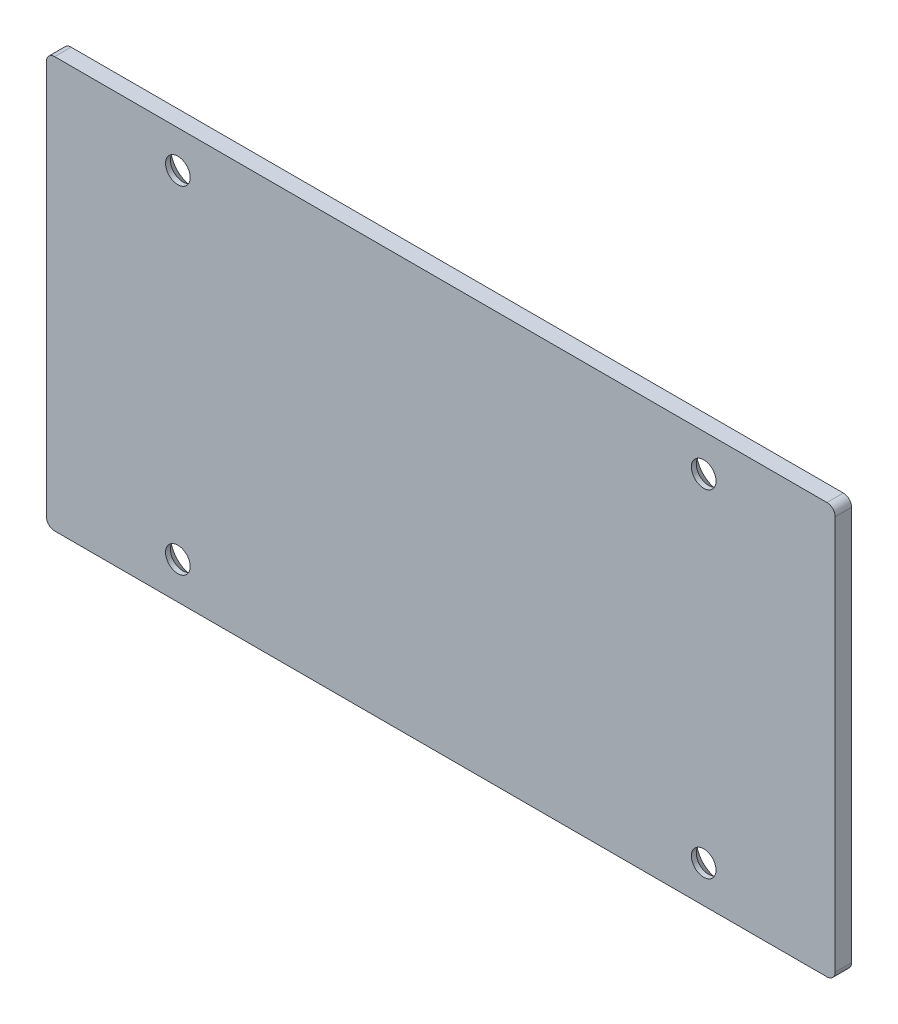
SolidWorks part; units mm, degrees
ref_plane "Спереди" through (0, 0, 0) normal (0, 0, 1) x (1, 0, 0)
ref_plane "Сверху" through (0, 0, 0) normal (0, 1, 0) x (1, 0, 0)
ref_plane "Справа" through (0, 0, 0) normal (1, 0, 0) x (0, 0, -1)
sketch "Эскиз1" plane through (0, 0, 60.7538) normal (0, 0, -1) x (-1, 0, 0)
  line L0 (-84.5501, 64.5438) -> (-84.5501, 29.5438)
  line L17 (-1.5112, 29.1447) -> (-7.5891, 29.1447)
  line L18 (-9.3198, 24.0438) -> (-63.7804, 24.0438)
  line L19 (-73.3198, 24.0438) -> (-82.5501, 24.0438)
  line L20 (-82.5501, 24.0438) -> (-82.5501, 29.5438)
  line L21 (-82.5501, 29.5438) -> (-84.5501, 29.5438)
  line L22 (-84.5501, 29.5438) -> (-84.5501, 23.0438)
  line L23 (-83.5501, 22.0438) -> (10.4499, 22.0438)
  line L24 (11.4499, 23.0438) -> (11.4499, 71.0438)
  line L25 (10.4499, 72.0438) -> (-83.5501, 72.0438)
  line L26 (-84.5501, 71.0438) -> (-84.5501, 64.5438)
  line L27 (-84.5501, 64.5438) -> (-82.5501, 64.5438)
  line L28 (-82.5501, 64.5438) -> (-82.5501, 70.0438)
  line L29 (-82.5501, 70.0438) -> (-73.3198, 70.0438)
  line L31 (0.2196, 70.0438) -> (9.4499, 70.0438)
  line L32 (9.4499, 70.0438) -> (9.4499, 24.0438)
  line L33 (9.4499, 24.0438) -> (0.2196, 24.0438)
  line L35 (-63.7804, 70.0438) -> (-9.3198, 70.0438)
  line L39 (-84.5501, 29.5438) -> (-84.5501, 23.0438)
  line L40 (-83.5501, 22.0438) -> (10.4499, 22.0438)
  line L41 (11.4499, 23.0438) -> (11.4499, 71.0438)
  line L42 (10.4499, 72.0438) -> (-83.5501, 72.0438)
  line L43 (-84.5501, 71.0438) -> (-84.5501, 64.5438)
  circle A0 centre (-4.5501, 67.5438) radius 1.5
  circle A1 centre (-68.5501, 67.5438) radius 1.5
  circle A2 centre (-68.5501, 26.5438) radius 1.5
  circle A3 centre (-4.5501, 26.5438) radius 1.5
  arc A9 (-0.7344, 25.3438) -> (-1.5112, 29.1447) centre (-4.5501, 26.5438) ccw
  arc A10 (-7.5891, 29.1447) -> (-8.3659, 25.3438) centre (-4.5501, 26.5438) ccw
  arc A11 (-64.7344, 25.3438) -> (-72.3659, 25.3438) centre (-68.5501, 26.5438) ccw
  arc A12 (-84.5501, 23.0438) -> (-83.5501, 22.0438) centre (-83.5501, 23.0438) ccw
  arc A13 (10.4499, 22.0438) -> (11.4499, 23.0438) centre (10.4499, 23.0438) ccw
  arc A14 (11.4499, 71.0438) -> (10.4499, 72.0438) centre (10.4499, 71.0438) ccw
  arc A15 (-83.5501, 72.0438) -> (-84.5501, 71.0438) centre (-83.5501, 71.0438) ccw
  arc A16 (-72.3659, 68.7438) -> (-64.7344, 68.7438) centre (-68.5501, 67.5438) ccw
  arc A17 (-8.3659, 68.7438) -> (-0.7344, 68.7438) centre (-4.5501, 67.5438) ccw
  arc A21 (-84.5501, 23.0438) -> (-83.5501, 22.0438) centre (-83.5501, 23.0438) ccw
  arc A22 (10.4499, 22.0438) -> (11.4499, 23.0438) centre (10.4499, 23.0438) ccw
  arc A23 (11.4499, 71.0438) -> (10.4499, 72.0438) centre (10.4499, 71.0438) ccw
  arc A24 (-83.5501, 72.0438) -> (-84.5501, 71.0438) centre (-83.5501, 71.0438) ccw
  arc A34 (-9.3198, 24.0438) -> (-8.3659, 25.3438) centre (-9.3198, 25.0438) ccw
  arc A36 (-64.7344, 25.3438) -> (-63.7804, 24.0438) centre (-63.7804, 25.0438) ccw
  arc A38 (-73.3198, 24.0438) -> (-72.3659, 25.3438) centre (-73.3198, 25.0438) ccw
  arc A40 (-72.3659, 68.7438) -> (-73.3198, 70.0438) centre (-73.3198, 69.0438) ccw
  arc A42 (-63.7804, 70.0438) -> (-64.7344, 68.7438) centre (-63.7804, 69.0438) ccw
  arc A44 (-8.3659, 68.7438) -> (-9.3198, 70.0438) centre (-9.3198, 69.0438) ccw
  arc A46 (0.2196, 70.0438) -> (-0.7344, 68.7438) centre (0.2196, 69.0438) ccw
  arc A48 (-0.7344, 25.3438) -> (0.2196, 24.0438) centre (0.2196, 25.0438) ccw
  dimension "D2" = 3
  dimension "D1" = 0
extrude "Бобышка-Вытянуть2" add sketch "Эскиз1" along normal blind 2
chamfer "Фаска1" distance 1.4 angle 45 4 edges at (67.0501, 26.5438, 58.7538) (3.0501, 26.5438, 58.7538) (3.0501, 67.5438, 58.7538) (67.0501, 67.5438, 58.7538)
sketch "Эскиз2" plane through (0, 0, 60.7538) normal (0, 0, 1) x (1, 0, 0)
  line L0 (78.3302, 72.0438) -> (78.3302, 22.0438) construction
  line L1 (-10.4499, 72.0438) -> (83.5501, 72.0438) construction
  line L2 (83.5501, 22.0438) -> (-10.4499, 22.0438) construction
